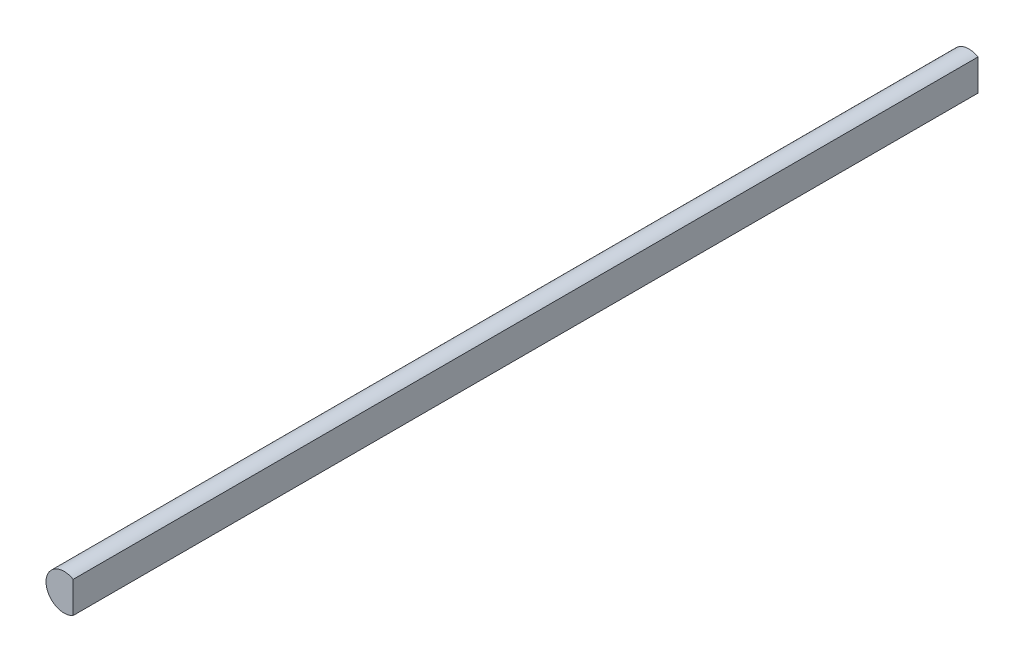
SolidWorks part; units mm, degrees
ref_plane "前视基准面" through (0, 0, 0) normal (0, 0, 1) x (1, 0, 0)
ref_plane "上视基准面" through (0, 0, 0) normal (0, 1, 0) x (1, 0, 0)
ref_plane "右视基准面" through (0, 0, 0) normal (1, 0, 0) x (0, 0, -1)
sketch "草图1" plane through (0, 0, 0) normal (0, 0, 1) x (1, 0, 0)
  line L0 (1, 1.7321) -> (1, -1.7321)
  arc A0 (1, 1.7321) -> (1, -1.7321) centre (0, 0) ccw
  dimension "D1" = 4
  dimension "D2" = 1
extrude "凸台-拉伸1" add sketch "草图1" along normal mid plane 100
